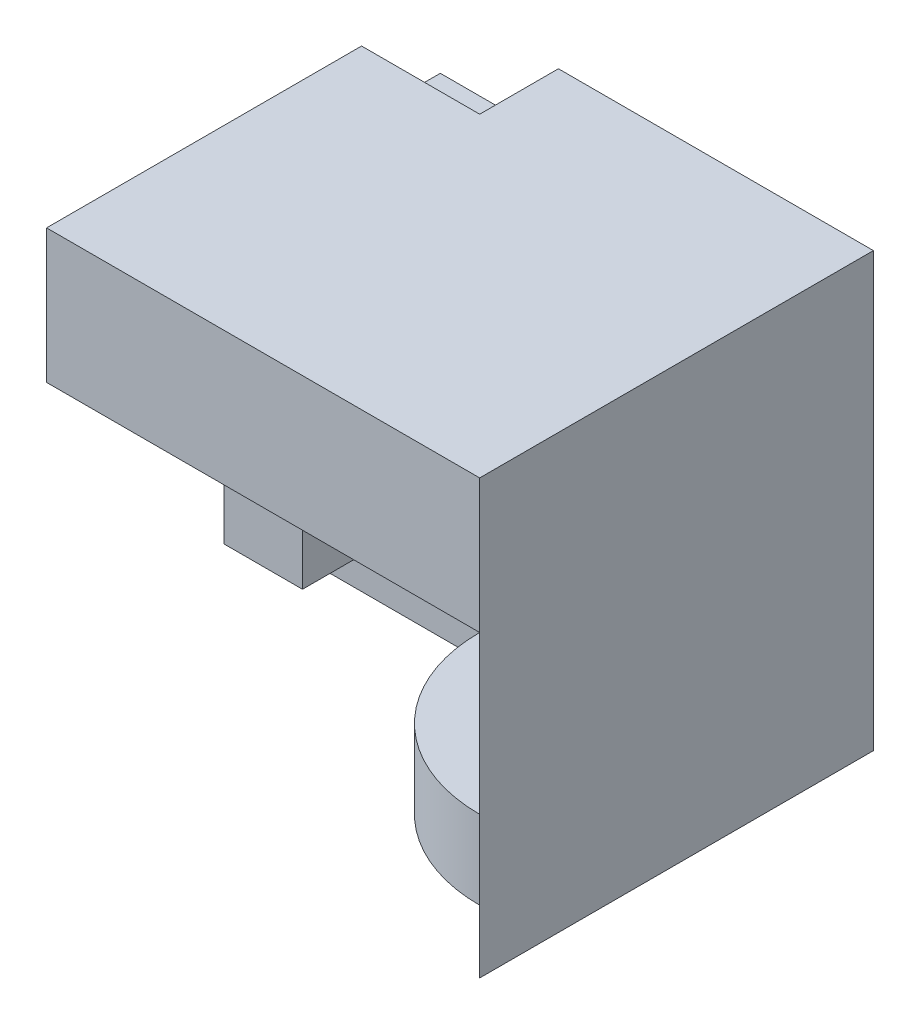
SolidWorks part; units mm, degrees
ref_plane "Спереди" through (0, 0, 0) normal (0, 0, 1) x (1, 0, 0)
ref_plane "Сверху" through (0, 0, 0) normal (0, 1, 0) x (1, 0, 0)
ref_plane "Справа" through (0, 0, 0) normal (1, 0, 0) x (0, 0, -1)
sketch "Эскиз1" plane through (0, 0, 0) normal (0, 0, 1) x (1, 0, 0)
  line L1 (-27.5, -27.5) -> (27.5, -27.5)
  line L2 (-27.5, -27.5) -> (-27.5, 27.5)
  line L3 (-27.5, 27.5) -> (27.5, 27.5)
  line L4 (27.5, -27.5) -> (27.5, 27.5)
  line L5 (-27.5, -27.5) -> (27.5, 27.5) construction
  line L6 (-27.5, 27.5) -> (27.5, -27.5) construction
  point P0 (0, 0)
  dimension "D1" = 55
extrude "Бобышка-Вытянуть1" add sketch "Эскиз1" along normal blind 50
sketch "Эскиз2" plane through (0, -27.5, 0) normal (0, -1, 0) x (1, 0, 0)
  line L0 (-27.5, 15) -> (7.5, 15)
  line L1 (-27.5, 50) -> (-27.5, 0) construction
  line L2 (7.5, 15) -> (7.5, 30)
  line L3 (7.5, 30) -> (27.5, 50)
  line L4 (27.5, 50) -> (-27.5, 50)
  line L5 (-27.5, 50) -> (-27.5, 15)
  dimension "D1" = 35
  dimension "D2" = 35
  dimension "D3" = 45
extrude "Вырез-Вытянуть1" cut sketch "Эскиз2" against normal blind 38
sketch "Эскиз3" plane through (-27.5, 0, 0) normal (-1, 0, 0) x (0, 0, 1)
  line L0 (50, 10.5) -> (15, -13.5)
  line L1 (15, 10.5) -> (15, -27.5) construction
  line L2 (15, -27.5) -> (0, -27.5) construction
  line L3 (15, -13.5) -> (15, 10.5)
  line L4 (15, 10.5) -> (50, 10.5)
  dimension "D1" = 14
extrude "Бобышка-Вытянуть2" add sketch "Эскиз3" against normal up to surface (55 mm away) up to face at (27.5, 2.1, 30)
sketch "Эскиз4" plane through (-27.5, 0, 0) normal (-1, 0, 0) x (0, 0, 1)
  line L0 (32.5, -1.5) -> (32.5, -13.5)
  line L1 (15, -13.5) -> (50, 10.5) construction
  line L2 (32.5, -13.5) -> (15, -13.5)
  line L3 (15, -13.5) -> (32.5, -1.5)
  dimension "D1" = 12
extrude "Бобышка-Вытянуть3" add sketch "Эскиз4" against normal blind 10 from offset 5 offset against normal yes
sketch "Эскиз5" plane through (0, -27.5, 0) normal (0, -1, 0) x (1, 0, 0)
  line L1 (27.5, 50) -> (27.5, 0) construction
  line L2 (27.5, 50) -> (7.5, 30)
  arc A0 (7.5, 30) -> (27.5, 50) centre (27.5, 30) cw
extrude "Бобышка-Вытянуть4" add sketch "Эскиз5" against normal blind 10 from offset 8 offset against normal yes
sketch "Эскиз6" plane through (-27.5, 0, 0) normal (-1, 0, 0) x (0, 0, 1)
  line L1 (0, 27.5) -> (10, 27.5)
  line L2 (0, 27.5) -> (0, 19.5)
  line L3 (0, 19.5) -> (10, 19.5)
  line L4 (10, 27.5) -> (10, 19.5)
  dimension "D1" = 10
  dimension "D2" = 8
extrude "Вырез-Вытянуть2" cut sketch "Эскиз6" against normal blind 15
